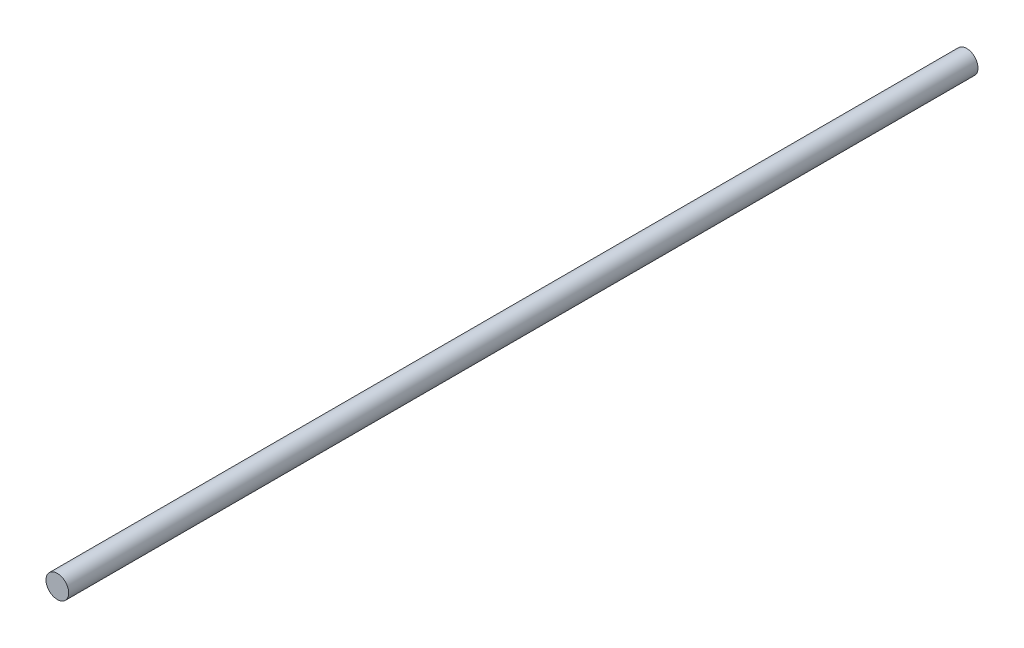
SolidWorks part; units mm, degrees
ref_plane "Ön Düzlem" through (0, 0, 0) normal (0, 0, 1) x (1, 0, 0)
ref_plane "Üst Düzlem" through (0, 0, 0) normal (0, 1, 0) x (1, 0, 0)
ref_plane "Sağ Düzlem" through (0, 0, 0) normal (1, 0, 0) x (0, 0, -1)
sketch "Çizim1" plane through (0, 0, 0) normal (0, 0, 1) x (1, 0, 0)
  circle A0 centre (0, 0) radius 6
  dimension "D1" = 12
extrude "Yükseklik-Ekstrüzyon1" add sketch "Çizim1" along normal blind 480 contours A0
